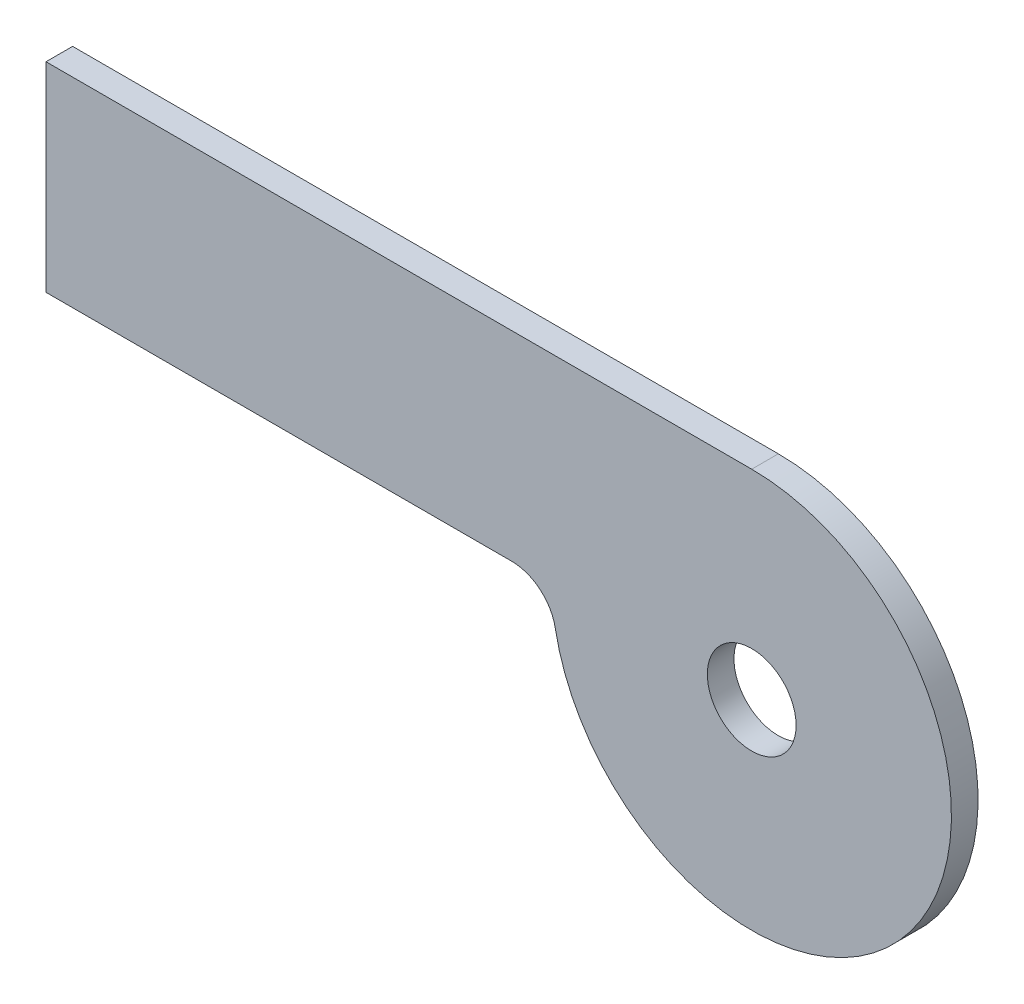
SolidWorks part; units mm, degrees
ref_plane "Front Plane" through (0, 0, 0) normal (0, 0, 1) x (1, 0, 0)
ref_plane "Top Plane" through (0, 0, 0) normal (0, 1, 0) x (1, 0, 0)
ref_plane "Right Plane" through (0, 0, 0) normal (1, 0, 0) x (0, 0, -1)
sketch "Sketch1" plane through (0, 0, 0) normal (0, 0, 1) x (1, 0, 0)
  line L22 (0, 22.5) -> (-22.5, 0)
  line L23 (-22.5, 0) -> (-22.5, 22.5)
  line L24 (-22.5, 22.5) -> (0, 22.5)
  line L25 (-27.0416, 0) -> (-22.5, 0)
  line L26 (-22.5, 22.5) -> (-79.5, 22.5)
  line L27 (-22.5, 22.5) -> (-22.5, 0)
  line L28 (-22.5, 0) -> (-79.5, 0)
  line L29 (-79.5, 22.5) -> (-79.5, 0)
  line L30 (-22.5, 0) -> (-22.125, -4.0909)
  circle A0 centre (0, 0) radius 22.5
  arc A9 (-27.0416, 0) -> (-22.125, -4.0909) centre (-27.0416, -5) cw
  circle A10 centre (0, 0) radius 5
  dimension "D1" = 45
  dimension "D11" = 5
  dimension "D2" = 10
  dimension "D10" = 57
extrude "Boss-Extrude2" add sketch "Sketch1" along normal blind 3 contours L26 L29 L28 L25 L23 | A0 L24 L23 | L22 A0 | A10
